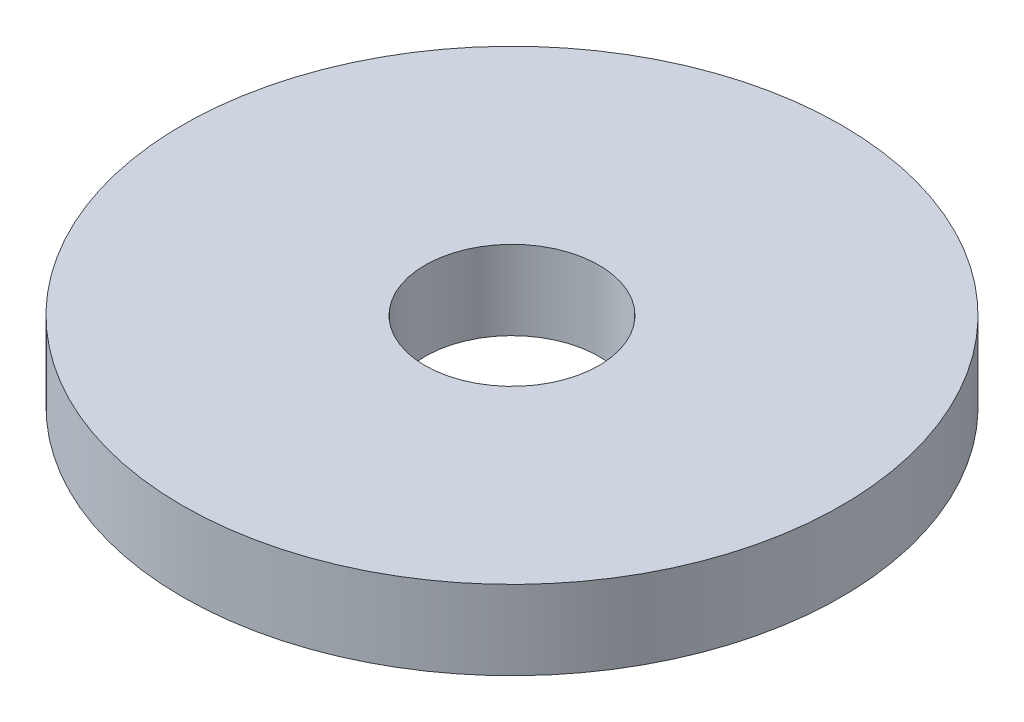
SolidWorks part; units mm, degrees
ref_plane "Plano frontal" through (0, 0, 0) normal (0, 0, 1) x (1, 0, 0)
ref_plane "Plano superior" through (0, 0, 0) normal (0, 1, 0) x (1, 0, 0)
ref_plane "Plano direito" through (0, 0, 0) normal (1, 0, 0) x (0, 0, -1)
sketch "Esboço1" plane through (0, 0, 0) normal (0, 1, 0) x (1, 0, 0)
  circle A0 centre (0, 0) radius 12.5
  dimension "D1" = 25
extrude "Ressalto-extrusão1" add sketch "Esboço1" along normal blind 3
hole_wizard "Furo com folga de M61" positions "Esboço2" profile "Esboço3" hole size "M6" standard "ISO" end condition through all
sketch "Esboço2" plane through (0, 3, 0) normal (0, 1, 0) x (1, 0, 0)
  point P0 (0, 0)
sketch "Esboço3" plane through (0, 3, 0) normal (1, 0, 0) x (0, 0, 1)
  line L0 (0, 0) -> (0, 3)
  line L1 (0, 3) -> (3.3, 3)
  line L2 (3.3, 3) -> (3.3, 0)
  line L5 (3.3, 0) -> (0, 0)
  line L11 (0, -6.35) -> (0, 107.95) construction
  dimension "Thru Hole Dia." = 6.6
  dimension "Thru Hole Depth" = 3
